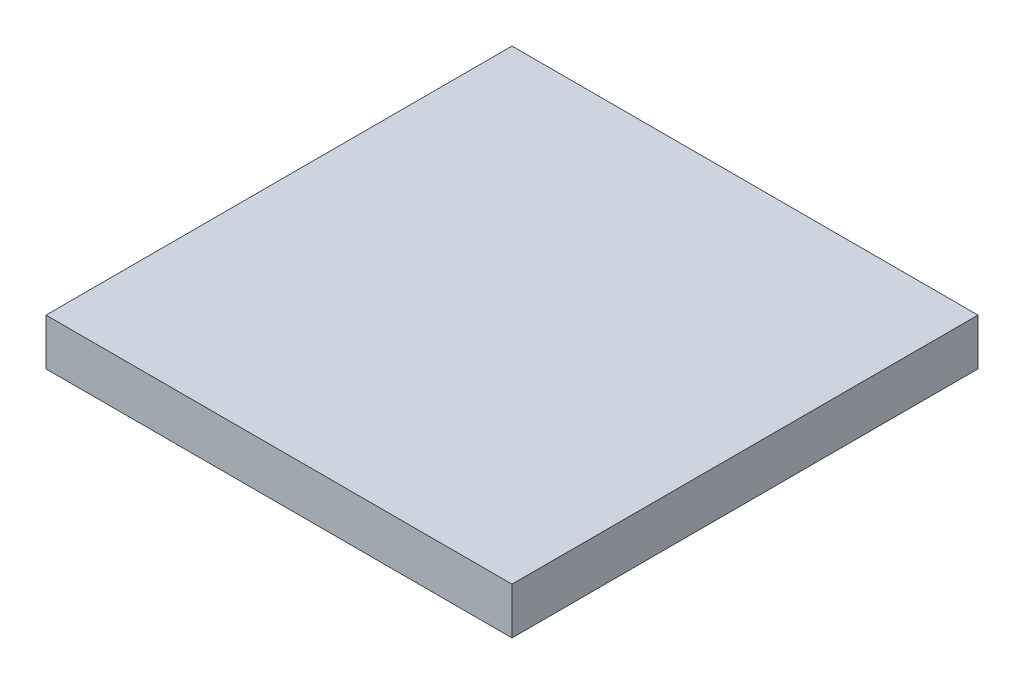
SolidWorks part; units mm, degrees
ref_plane "前视基准面" through (0, 0, 0) normal (0, 0, 1) x (1, 0, 0)
ref_plane "上视基准面" through (0, 0, 0) normal (0, 1, 0) x (1, 0, 0)
ref_plane "右视基准面" through (0, 0, 0) normal (1, 0, 0) x (0, 0, -1)
other "Configuration Table"
sketch "草图1" plane through (0, 0, 0) normal (0, 1, 0) x (1, 0, 0)
  line L1 (0, 0) -> (20, 0)
  line L2 (0, 0) -> (0, 20)
  line L3 (0, 20) -> (20, 20)
  line L4 (20, 0) -> (20, 20)
  line L5 (0, 0) -> (20, 20) construction
  line L6 (0, 20) -> (20, 0) construction
  point P4 (10, 10)
  dimension "D1" = 20
  dimension "D2" = 20
extrude "凸台-拉伸1" add sketch "草图1" along normal blind 2
